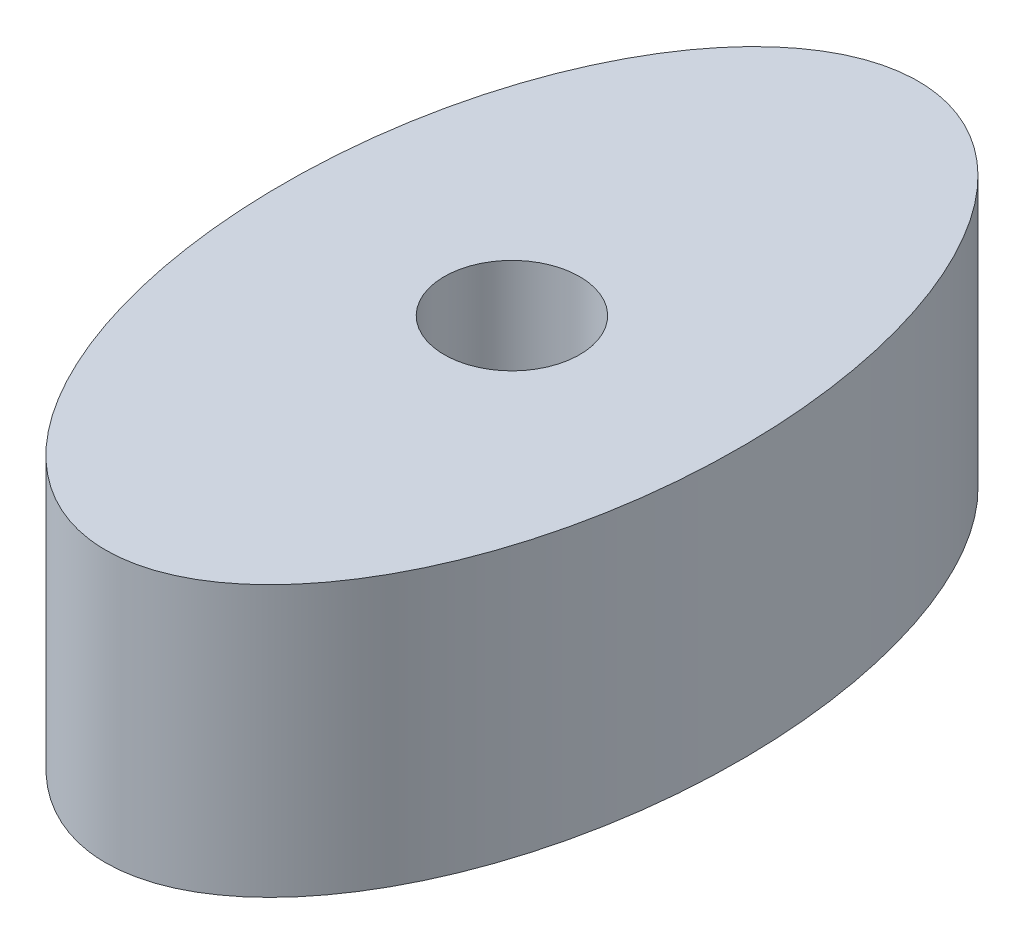
SolidWorks part; units mm, degrees
ref_plane "前视基准面" through (0, 0, 0) normal (0, 0, 1) x (1, 0, 0)
ref_plane "上视基准面" through (0, 0, 0) normal (0, 1, 0) x (1, 0, 0)
ref_plane "右视基准面" through (0, 0, 0) normal (1, 0, 0) x (0, 0, -1)
sketch "草图1" plane through (0, 0, 0) normal (0, 1, 0) x (1, 0, 0)
  circle A0 centre (0, 0) radius 13.5
  ellipse E0 centre (0, 0) end of major axis (0, -24) minor radius 13.5
  dimension "D1" = 27
  dimension "D2" = 24
extrude "凸台-拉伸1" add sketch "草图1" along normal blind 16 contours E0
sketch "草图2" plane through (0, 0, 0) normal (0, -1, 0) x (1, 0, 0)
  circle A0 centre (0, 0) radius 4
  dimension "D1" = 8
extrude "切除-拉伸1" cut sketch "草图2" against normal through all
